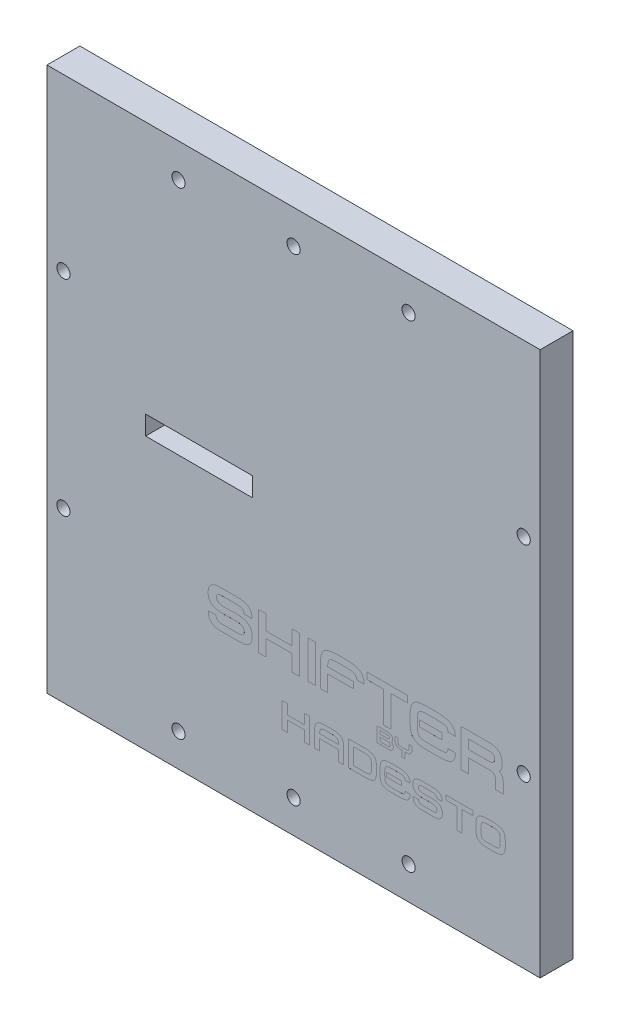
SolidWorks part; units mm, degrees
material "Oak"
ref_plane "Front Plane" through (0, 0, 0) normal (0, 0, 1) x (1, 0, 0)
ref_plane "Top Plane" through (0, 0, 0) normal (0, 1, 0) x (1, 0, 0)
ref_plane "Right Plane" through (0, 0, 0) normal (1, 0, 0) x (0, 0, -1)
sketch "Szkic1" plane through (0, 0, 0) normal (0, 1, 0) x (1, 0, 0)
  line L1 (-75, -5) -> (75, -5)
  line L2 (-75, -5) -> (-75, 5)
  line L3 (-75, 5) -> (75, 5)
  line L4 (75, -5) -> (75, 5)
  line L5 (-75, -5) -> (75, 5) construction
  line L6 (-75, 5) -> (75, -5) construction
  point P0 (0, 0)
extrude "Dodanie-wyciągnięcie1" add sketch "Szkic1" along normal blind 165.5
sketch "Szkic2" plane through (0, 0, 5) normal (0, 0, 1) x (1, 0, 0)
  line L0 (-75, 165.5) -> (-75, 155) construction
  line L1 (-75, 165.5) -> (-75, 0) construction
  line L2 (-35, 155.5) -> (-35, 155.25) construction
  line L3 (0, 155.5) -> (0, 155.25) construction
  line L4 (35, 155.5) -> (35, 155.25) construction
  line L5 (75, 0) -> (75, 10) construction
  line L6 (75, 165.5) -> (75, 0) construction
  line L7 (75, 10) -> (35, 10) construction
  line L8 (35, 10) -> (0, 10) construction
  line L9 (0, 10) -> (-35, 10) construction
  line L10 (-75, 155) -> (-75, 145) construction
  line L11 (-75, 145) -> (-70, 145) construction
  line L12 (-70, 145) -> (-70, 113.75) construction
  line L13 (-70, 113.75) -> (-70, 51.25) construction
  line L14 (75, 10) -> (75, 20) construction
  line L15 (75, 20) -> (70, 20) construction
  line L16 (70, 20) -> (70, 51.25) construction
  line L17 (70, 51.25) -> (70, 113.75) construction
  line L18 (-35, 165.5) -> (-35, 155.5) construction
  line L19 (-75, 165.5) -> (75, 165.5) construction
  line L20 (0, 165.5) -> (0, 155.5) construction
  line L21 (35, 165.5) -> (35, 155.5) construction
  circle A3 centre (-35, 10) radius 2
  circle A4 centre (0, 10) radius 2
  circle A5 centre (35, 10) radius 2
  circle A6 centre (-70, 113.75) radius 2
  circle A7 centre (-70, 51.25) radius 2
  circle A8 centre (70, 113.75) radius 2
  circle A9 centre (70, 51.25) radius 2
  circle A13 centre (-35, 155.25) radius 2
  circle A14 centre (0, 155.25) radius 2
  circle A15 centre (35, 155.25) radius 2
sketch "Szkic3" plane through (0, 0, 5) normal (0, 0, 1) x (1, 0, 0)
  line L0 (-16.5425, 42.8324) -> (-22.1233, 42.8324)
  line L1 (-25.9282, 46.2952) -> (-23.5548, 46.2952)
  line L2 (-21.7883, 44.8332) -> (-16.9713, 44.8332)
  line L3 (-22.1537, 54.2751) -> (-16.8447, 54.2751)
  line L4 (-12.6205, 50.8264) -> (-15.0712, 50.8264)
  line L5 (-17.0205, 52.2883) -> (-22.0272, 52.2883)
  line L6 (1.875, 42.8324) -> (-0.4656, 42.8324)
  line L7 (-0.4656, 42.8324) -> (-0.4656, 47.7431)
  line L8 (-0.4656, 47.7431) -> (-8.3283, 47.7431)
  line L9 (-8.3283, 47.7431) -> (-8.3283, 42.8324)
  line L10 (-8.3283, 42.8324) -> (-10.6689, 42.8324)
  line L11 (-10.6689, 42.8324) -> (-10.6689, 54.2751)
  line L12 (-10.6689, 54.2751) -> (-8.3283, 54.2751)
  line L13 (-8.3283, 54.2751) -> (-8.3283, 49.7275)
  line L14 (-8.3283, 49.7275) -> (-0.4656, 49.7275)
  line L15 (-0.4656, 49.7275) -> (-0.4656, 54.2751)
  line L16 (-0.4656, 54.2751) -> (1.875, 54.2751)
  line L17 (1.875, 54.2751) -> (1.875, 42.8324)
  line L18 (6.706, 42.8324) -> (4.3655, 42.8324)
  line L19 (4.3655, 42.8324) -> (4.3655, 54.2751)
  line L20 (4.3655, 54.2751) -> (6.706, 54.2751)
  line L21 (6.706, 54.2751) -> (6.706, 42.8324)
  line L22 (10.3539, 49.6807) -> (18.205, 49.6807)
  line L23 (18.205, 49.6807) -> (18.205, 47.7759)
  line L24 (18.205, 47.7759) -> (10.3539, 47.7759)
  line L25 (10.3539, 47.7759) -> (10.3539, 42.8324)
  line L26 (10.3539, 42.8324) -> (8.1235, 42.8324)
  line L27 (8.1235, 42.8324) -> (8.1399, 48.767)
  line L28 (13.7089, 54.3384) -> (15.7754, 54.3384)
  line L29 (21.5108, 50.653) -> (19.2944, 50.653)
  line L30 (15.6957, 52.3047) -> (13.8214, 52.3047)
  line L31 (34.6708, 52.2743) -> (29.6477, 52.2743)
  line L32 (29.6477, 52.2743) -> (29.6477, 42.8324)
  line L33 (29.6477, 42.8324) -> (27.3071, 42.8324)
  line L34 (27.3071, 42.8324) -> (27.3071, 52.2743)
  line L35 (27.3071, 52.2743) -> (22.3003, 52.2743)
  line L36 (22.3003, 52.2743) -> (22.3003, 54.2751)
  line L37 (22.3003, 54.2751) -> (34.6708, 54.2751)
  line L38 (34.6708, 54.2751) -> (34.6708, 52.2743)
  line L39 (43.4309, 42.8324) -> (40.9685, 42.8324)
  line L40 (40.999, 54.322) -> (43.4637, 54.322)
  line L41 (49.1991, 50.7467) -> (46.9523, 50.7467)
  line L42 (43.3841, 52.3211) -> (41.1115, 52.3211)
  line L43 (37.6252, 49.5284) -> (37.6276, 47.9235)
  line L44 (41.0623, 44.8004) -> (43.4005, 44.8004)
  line L45 (46.9687, 46.4217) -> (49.2296, 46.4217)
  line L46 (45.1764, 47.7759) -> (38.3328, 47.7993)
  line L47 (38.3328, 47.7993) -> (38.3328, 49.6971)
  line L48 (38.3328, 49.6971) -> (45.1764, 49.6971)
  line L49 (45.1764, 49.6971) -> (45.1764, 47.7759)
  line L50 (63.7883, 42.8324) -> (61.4642, 42.8324)
  line L51 (61.4642, 42.8324) -> (61.4642, 45.016)
  line L52 (59.4516, 47.1082) -> (53.2664, 47.0918)
  line L53 (53.2664, 47.0918) -> (53.2664, 42.8324)
  line L54 (53.2664, 42.8324) -> (50.9891, 42.8324)
  line L55 (50.9891, 42.8324) -> (50.9891, 54.2751)
  line L56 (50.9891, 54.2751) -> (59.2923, 54.2751)
  line L57 (63.7883, 45.7634) -> (63.7883, 42.8324)
  line L58 (59.468, 52.0681) -> (53.2664, 52.0681)
  line L59 (53.2664, 52.0681) -> (53.2664, 49.2988)
  line L60 (53.2664, 49.2988) -> (59.468, 49.2988)
  line L61 (4.9001, 26.251) -> (3.3398, 26.251)
  line L62 (3.3398, 26.251) -> (3.3398, 29.5248)
  line L63 (3.3398, 29.5248) -> (-1.9021, 29.5248)
  line L64 (-1.9021, 29.5248) -> (-1.9021, 26.251)
  line L65 (-1.9021, 26.251) -> (-3.4624, 26.251)
  line L66 (-3.4624, 26.251) -> (-3.4624, 33.8794)
  line L67 (-3.4624, 33.8794) -> (-1.9021, 33.8794)
  line L68 (-1.9021, 33.8794) -> (-1.9021, 30.8477)
  line L69 (-1.9021, 30.8477) -> (3.3398, 30.8477)
  line L70 (3.3398, 30.8477) -> (3.3398, 33.8794)
  line L71 (3.3398, 33.8794) -> (4.9001, 33.8794)
  line L72 (4.9001, 33.8794) -> (4.9001, 26.251)
  line L73 (7.9396, 30.8477) -> (13.6922, 30.8477)
  line L74 (11.5133, 32.5455) -> (9.9983, 32.5455)
  line L75 (13.7016, 29.5248) -> (7.9412, 29.5248)
  line L76 (7.9412, 29.5248) -> (7.9412, 26.251)
  line L77 (7.9412, 26.251) -> (6.3808, 26.251)
  line L78 (6.3808, 26.251) -> (6.3808, 30.7587)
  line L79 (9.828, 33.8794) -> (11.7039, 33.8794)
  line L80 (15.2635, 30.7587) -> (15.2635, 26.251)
  line L81 (15.2635, 26.251) -> (13.7016, 26.251)
  line L82 (13.7016, 26.251) -> (13.7016, 29.5248)
  line L83 (21.9892, 26.24) -> (16.6552, 26.24)
  line L84 (16.6552, 26.24) -> (16.6552, 33.8794)
  line L85 (16.6552, 33.8794) -> (21.8096, 33.8794)
  line L86 (23.7011, 29.6138) -> (23.7011, 30.5463)
  line L87 (21.7252, 32.5549) -> (18.2265, 32.5549)
  line L88 (18.2265, 32.5549) -> (18.2265, 27.5739)
  line L89 (18.2265, 27.5739) -> (21.8205, 27.5739)
  line L90 (31.6044, 26.251) -> (29.9629, 26.251)
  line L91 (29.9832, 33.9107) -> (31.6263, 33.9107)
  line L92 (35.4499, 31.5272) -> (33.952, 31.5272)
  line L93 (31.5732, 32.5768) -> (30.0581, 32.5768)
  line L94 (27.734, 30.715) -> (27.7355, 29.645)
  line L95 (30.0253, 27.563) -> (31.5841, 27.563)
  line L96 (33.963, 28.6438) -> (35.4702, 28.6438)
  line L97 (32.7681, 29.5466) -> (28.2057, 29.5623)
  line L98 (28.2057, 29.5623) -> (28.2057, 30.8337)
  line L99 (28.2057, 30.8337) -> (32.7681, 30.8274)
  line L100 (32.7681, 30.8274) -> (32.7681, 29.5466)
  line L101 (42.6036, 26.251) -> (38.883, 26.251)
  line L102 (36.3465, 28.5595) -> (37.9287, 28.5595)
  line L103 (39.1064, 27.5848) -> (42.3177, 27.5848)
  line L104 (38.8627, 33.8794) -> (42.4021, 33.8794)
  line L105 (45.2182, 31.5803) -> (43.5845, 31.5803)
  line L106 (42.2849, 32.5549) -> (38.9471, 32.5549)
  line L107 (54.5539, 32.5455) -> (51.2051, 32.5455)
  line L108 (51.2051, 32.5455) -> (51.2051, 26.251)
  line L109 (51.2051, 26.251) -> (49.6447, 26.251)
  line L110 (49.6447, 26.251) -> (49.6447, 32.5455)
  line L111 (49.6447, 32.5455) -> (46.3069, 32.5455)
  line L112 (46.3069, 32.5455) -> (46.3069, 33.8794)
  line L113 (46.3069, 33.8794) -> (54.5539, 33.8794)
  line L114 (54.5539, 33.8794) -> (54.5539, 32.5455)
  line L115 (60.5002, 26.251) -> (59.1335, 26.251)
  line L116 (59.1538, 33.9216) -> (60.5111, 33.9216)
  line L117 (62.8477, 29.6888) -> (62.8477, 30.3979)
  line L118 (60.458, 32.4815) -> (59.2287, 32.4815)
  line L119 (57.0014, 30.3885) -> (57.0014, 29.6778)
  line L120 (59.1975, 27.6692) -> (60.4783, 27.6692)
  spline S0 degree 3 poles (-12.5713, 46.2577) (-12.5722, 45.9664) (-12.5971, 45.5408) (-12.7128, 45.0029) (-12.83, 44.6437) (-12.9796, 44.3159) (-13.2238, 43.9226) (-13.462, 43.6722) (-13.6397, 43.5306) knots 0 0 0 0 0.288468 0.419708 0.543339 0.661573 0.775414 1 1 1 1
  spline S1 degree 3 poles (-13.6397, 43.5306) (-13.7956, 43.405) (-14.0684, 43.2543) (-14.4678, 43.0951) (-14.8161, 43.0021) (-15.1968, 42.9241) (-15.7757, 42.8517) (-16.2289, 42.8331) (-16.5425, 42.8324) knots 0 0 0 0 0.196905 0.306371 0.424122 0.552441 0.690159 1 1 1 1
  spline S2 degree 3 poles (-22.1233, 42.8324) (-22.422, 42.8344) (-22.8582, 42.854) (-23.4142, 42.9477) (-23.7888, 43.04) (-24.1336, 43.1621) (-24.4483, 43.3123) (-24.7349, 43.4871) (-24.9872, 43.6949) (-25.2139, 43.9236) (-25.4089, 44.1827) (-25.5687, 44.4703) (-25.7049, 44.7826) (-25.8063, 45.1234) (-25.9058, 45.628) (-25.9273, 46.0244) (-25.9282, 46.2952) knots 0 0 0 0 0.151922 0.221135 0.286192 0.347689 0.406613 0.463101 0.517821 0.572256 0.62638 0.681995 0.739047 0.799173 0.862284 1 1 1 1
  spline S3 degree 3 poles (-23.5548, 46.2952) (-23.5548, 46.1808) (-23.5432, 46.0128) (-23.4942, 45.8007) (-23.4488, 45.6557) (-23.3843, 45.5245) (-23.3085, 45.4034) (-23.2203, 45.2915) (-23.1122, 45.1968) (-22.9959, 45.1079) (-22.8624, 45.037) (-22.7184, 44.9718) (-22.5586, 44.9215) (-22.3854, 44.8818) (-22.1277, 44.8442) (-21.9269, 44.8304) (-21.7883, 44.8332) knots 0 0 0 0 0.130945 0.191386 0.248712 0.304229 0.357995 0.411968 0.466331 0.521876 0.579035 0.638606 0.702429 0.770232 0.841588 1 1 1 1
  spline S4 degree 3 poles (-16.9713, 44.8332) (-16.8211, 44.8336) (-16.6038, 44.8417) (-16.3246, 44.8653) (-16.1399, 44.8953) (-15.9696, 44.9248) (-15.7743, 44.9853) (-15.6357, 45.0343) (-15.5538, 45.0816) knots 0 0 0 0 0.310015 0.449363 0.57828 0.696618 0.805875 1 1 1 1
  spline S5 degree 3 poles (-15.5538, 45.0816) (-15.4606, 45.1333) (-15.3318, 45.2304) (-15.1981, 45.3974) (-15.1156, 45.5375) (-15.0561, 45.6959) (-14.9882, 45.9333) (-14.9809, 46.1266) (-14.9775, 46.2577) knots 0 0 0 0 0.232178 0.345784 0.463842 0.584405 0.713048 1 1 1 1
  spline S6 degree 3 poles (-14.9775, 46.2577) (-14.9803, 46.4053) (-15.0015, 46.6269) (-15.1181, 46.8905) (-15.2304, 47.0659) (-15.3779, 47.2214) (-15.6263, 47.4094) (-15.8492, 47.5073) (-16.006, 47.5604) knots 0 0 0 0 0.249245 0.364726 0.480164 0.596826 0.721947 1 1 1 1
  spline S7 degree 3 poles (-16.006, 47.5604) (-16.1277, 47.6026) (-16.3234, 47.6529) (-16.6003, 47.7037) (-16.8364, 47.7359) (-17.0927, 47.7614) (-17.4737, 47.7879) (-17.7702, 47.7891) (-17.974, 47.7923) knots 0 0 0 0 0.194055 0.304223 0.424293 0.553298 0.692568 1 1 1 1
  spline S8 degree 3 poles (-17.974, 47.7923) (-18.1958, 47.7915) (-18.5622, 47.7871) (-19.0955, 47.7678) (-19.5742, 47.7525) (-20.053, 47.7372) (-20.5893, 47.7177) (-20.9589, 47.7135) (-21.1838, 47.7127) knots 0 0 0 0 0.207249 0.342309 0.498541 0.654773 0.789832 1 1 1 1
  spline S9 degree 3 poles (-21.1838, 47.7127) (-21.5213, 47.7157) (-22.0113, 47.7254) (-22.6409, 47.7824) (-23.0635, 47.8443) (-23.4542, 47.9175) (-23.9144, 48.0333) (-24.2341, 48.1563) (-24.431, 48.2515) knots 0 0 0 0 0.305274 0.442866 0.571301 0.691383 0.802203 1 1 1 1
  spline S10 degree 3 poles (-24.431, 48.2515) (-24.6786, 48.375) (-25.0201, 48.6072) (-25.3906, 49.003) (-25.6101, 49.3368) (-25.783, 49.7059) (-25.9488, 50.267) (-25.9946, 50.717) (-25.9914, 51.0255) knots 0 0 0 0 0.24616 0.363762 0.480638 0.600407 0.725359 1 1 1 1
  spline S11 degree 3 poles (-25.9914, 51.0255) (-25.9927, 51.3039) (-25.9626, 51.7098) (-25.8472, 52.2226) (-25.7313, 52.5649) (-25.5783, 52.8745) (-25.3286, 53.2434) (-25.0931, 53.4792) (-24.9137, 53.6074) knots 0 0 0 0 0.287332 0.417925 0.54153 0.659382 0.773151 1 1 1 1
  spline S12 degree 3 poles (-24.9137, 53.6074) (-24.7536, 53.7243) (-24.4854, 53.8727) (-24.0922, 54.0226) (-23.7601, 54.1144) (-23.3992, 54.1874) (-22.8619, 54.2559) (-22.4425, 54.2784) (-22.1537, 54.2751) knots 0 0 0 0 0.205829 0.317156 0.436985 0.563785 0.699798 1 1 1 1
  spline S13 degree 3 poles (-16.8447, 54.2751) (-16.514, 54.2729) (-16.032, 54.2538) (-15.4167, 54.1597) (-15.0024, 54.0678) (-14.6215, 53.9455) (-14.2721, 53.7988) (-13.9567, 53.623) (-13.6744, 53.4194) (-13.4246, 53.1899) (-13.2094, 52.9306) (-13.0252, 52.6466) (-12.8778, 52.333) (-12.7598, 51.9949) (-12.6489, 51.4922) (-12.6205, 51.0969) (-12.6205, 50.8264) knots 0 0 0 0 0.159185 0.231381 0.299177 0.363087 0.423506 0.481188 0.536339 0.590564 0.643901 0.697977 0.752917 0.810175 0.869863 1 1 1 1
  spline S14 degree 3 poles (-15.0712, 50.8264) (-15.0691, 50.9412) (-15.0855, 51.1087) (-15.1351, 51.3221) (-15.19, 51.4655) (-15.2574, 51.5988) (-15.3439, 51.7184) (-15.4411, 51.8304) (-15.5589, 51.9255) (-15.6873, 52.0143) (-15.8347, 52.085) (-15.9946, 52.1496) (-16.1706, 52.2) (-16.3616, 52.2402) (-16.646, 52.2769) (-16.8677, 52.2916) (-17.0205, 52.2883) knots 0 0 0 0 0.123736 0.18099 0.235951 0.289117 0.341746 0.394885 0.448749 0.504633 0.563073 0.624754 0.690648 0.760424 0.8353 1 1 1 1
  spline S15 degree 3 poles (-22.0272, 52.2883) (-22.2371, 52.2869) (-22.5405, 52.2592) (-22.8972, 52.1172) (-23.1063, 51.9741) (-23.2671, 51.7854) (-23.4277, 51.4644) (-23.4554, 51.1829) (-23.4587, 50.9927) knots 0 0 0 0 0.286177 0.406449 0.517602 0.626596 0.73942 1 1 1 1
  spline S16 degree 3 poles (-23.4587, 50.9927) (-23.457, 50.8857) (-23.4397, 50.7253) (-23.3611, 50.5294) (-23.2838, 50.394) (-23.1812, 50.2708) (-23.0548, 50.1609) (-22.908, 50.0593) (-22.739, 49.9686) (-22.5482, 49.8892) (-22.3348, 49.8213) (-22.0996, 49.7644) (-21.8419, 49.7141) (-21.5617, 49.6777) (-21.1439, 49.6434) (-20.8193, 49.6322) (-20.5957, 49.6338) knots 0 0 0 0 0.091833 0.135566 0.179508 0.224525 0.271785 0.322124 0.376754 0.435361 0.498446 0.567863 0.641921 0.722688 0.809065 1 1 1 1
  spline S17 degree 3 poles (-20.5957, 49.6338) (-20.3847, 49.6313) (-20.0411, 49.645) (-19.5468, 49.6639) (-19.1135, 49.688) (-18.6816, 49.71) (-18.1961, 49.7357) (-17.86, 49.7408) (-17.6554, 49.7439) knots 0 0 0 0 0.215037 0.3505 0.504367 0.657438 0.791346 1 1 1 1
  spline S18 degree 3 poles (-17.6554, 49.7439) (-17.3013, 49.7442) (-16.7871, 49.7276) (-16.1262, 49.6657) (-15.6825, 49.5961) (-15.2721, 49.5153) (-14.7902, 49.377) (-14.4514, 49.2483) (-14.2465, 49.1371) knots 0 0 0 0 0.304045 0.441512 0.569747 0.689567 0.800388 1 1 1 1
  spline S19 degree 3 poles (-14.2465, 49.1371) (-13.9801, 49.0015) (-13.6163, 48.7484) (-13.2176, 48.3282) (-12.9809, 47.9812) (-12.7966, 47.5998) (-12.617, 47.0288) (-12.5698, 46.5702) (-12.5713, 46.2577) knots 0 0 0 0 0.254404 0.37397 0.491718 0.610756 0.733649 1 1 1 1
  spline S20 degree 3 poles (8.1399, 48.767) (8.1362, 49.1295) (8.1517, 49.6538) (8.1869, 50.3257) (8.2303, 50.7693) (8.2805, 51.1728) (8.3587, 51.6344) (8.4451, 51.9562) (8.5124, 52.1548) knots 0 0 0 0 0.317801 0.45977 0.589762 0.708489 0.816214 1 1 1 1
  spline S21 degree 3 poles (8.5124, 52.1548) (8.5823, 52.3536) (8.7152, 52.6374) (8.9421, 52.982) (9.1387, 53.211) (9.3602, 53.4154) (9.6921, 53.6615) (9.973, 53.8027) (10.1688, 53.8815) knots 0 0 0 0 0.255571 0.378596 0.499596 0.620993 0.743641 1 1 1 1
  spline S22 degree 3 poles (10.1688, 53.8815) (10.3771, 53.968) (10.7195, 54.064) (11.2069, 54.1671) (11.6307, 54.227) (12.0937, 54.2803) (12.7906, 54.3259) (13.3339, 54.3388) (13.7089, 54.3384) knots 0 0 0 0 0.188097 0.296817 0.416308 0.545737 0.686461 1 1 1 1
  spline S23 degree 3 poles (15.7754, 54.3384) (16.2552, 54.3384) (16.9455, 54.3195) (17.8243, 54.2409) (18.3919, 54.1568) (18.9002, 54.0541) (19.464, 53.8884) (19.8483, 53.725) (20.0676, 53.5816) knots 0 0 0 0 0.326658 0.469759 0.60036 0.717142 0.822452 1 1 1 1
  spline S24 degree 3 poles (20.0676, 53.5816) (20.2708, 53.4493) (20.5514, 53.2043) (20.848, 52.7998) (21.047, 52.4533) (21.2078, 52.0614) (21.3982, 51.4654) (21.4729, 50.9844) (21.5108, 50.653) knots 0 0 0 0 0.215512 0.327131 0.444654 0.569708 0.702963 1 1 1 1
  spline S25 degree 3 poles (19.2944, 50.653) (19.2538, 50.8306) (19.1749, 51.0836) (19.0275, 51.3916) (18.8996, 51.5854) (18.756, 51.7535) (18.5427, 51.944) (18.3519, 52.0428) (18.219, 52.0892) knots 0 0 0 0 0.291344 0.422029 0.544637 0.661528 0.774774 1 1 1 1
  spline S26 degree 3 poles (18.219, 52.0892) (18.0932, 52.1354) (17.8772, 52.1774) (17.5622, 52.2242) (17.2667, 52.2535) (16.9315, 52.2767) (16.4035, 52.298) (15.9871, 52.3079) (15.6957, 52.3047) knots 0 0 0 0 0.157647 0.259244 0.376059 0.508256 0.65595 1 1 1 1
  spline S27 degree 3 poles (13.8214, 52.3047) (13.498, 52.3039) (13.0366, 52.294) (12.4539, 52.2529) (12.0876, 52.2099) (11.7694, 52.1513) (11.4332, 52.0702) (11.2106, 51.9812) (11.0896, 51.8994) knots 0 0 0 0 0.347896 0.496132 0.628134 0.744282 0.843901 1 1 1 1
  spline S28 degree 3 poles (11.0896, 51.8994) (10.9672, 51.823) (10.8144, 51.6538) (10.6572, 51.3775) (10.5595, 51.1174) (10.4778, 50.8178) (10.3906, 50.3365) (10.3615, 49.951) (10.3539, 49.6807) knots 0 0 0 0 0.177191 0.278825 0.393353 0.521096 0.66412 1 1 1 1
  spline S29 degree 3 poles (49.2296, 46.4217) (49.2301, 46.0648) (49.1922, 45.5471) (49.0255, 44.9035) (48.8535, 44.4908) (48.6344, 44.1265) (48.2729, 43.7059) (47.9248, 43.4733) (47.6762, 43.3549) knots 0 0 0 0 0.294114 0.424501 0.54583 0.660956 0.773103 1 1 1 1
  spline S30 degree 3 poles (47.6762, 43.3549) (47.4649, 43.2548) (47.1022, 43.1355) (46.5648, 43.0284) (46.0664, 42.9576) (45.5023, 42.8987) (44.6164, 42.847) (43.9185, 42.829) (43.4309, 42.8324) knots 0 0 0 0 0.16271 0.264982 0.381608 0.513497 0.660216 1 1 1 1
  spline S31 degree 3 poles (40.9685, 42.8324) (40.6006, 42.8331) (40.0683, 42.8441) (39.3856, 42.8848) (38.933, 42.9282) (38.5214, 42.9874) (38.0474, 43.0717) (37.7161, 43.1615) (37.5128, 43.2377) knots 0 0 0 0 0.315853 0.456902 0.58691 0.70608 0.813768 1 1 1 1
  spline S32 degree 3 poles (37.5128, 43.2377) (37.3157, 43.308) (37.0371, 43.4466) (36.699, 43.6791) (36.4767, 43.8806) (36.2743, 44.102) (36.0373, 44.4384) (35.8937, 44.7167) (35.8212, 44.9152) knots 0 0 0 0 0.254655 0.377777 0.499186 0.619886 0.74278 1 1 1 1
  spline S33 degree 3 poles (35.8212, 44.9152) (35.744, 45.1184) (35.6573, 45.4504) (35.5668, 45.9233) (35.5137, 46.3359) (35.4646, 46.7879) (35.4262, 47.4708) (35.4136, 48.003) (35.4135, 48.371) knots 0 0 0 0 0.186213 0.294014 0.413081 0.543143 0.684177 1 1 1 1
  spline S34 degree 3 poles (35.4135, 48.371) (35.4129, 48.7639) (35.4211, 49.3305) (35.4592, 50.0561) (35.499, 50.5326) (35.5472, 50.9657) (35.6223, 51.4555) (35.7024, 51.7975) (35.7673, 52.0072) knots 0 0 0 0 0.321609 0.463729 0.594587 0.712971 0.820379 1 1 1 1
  spline S35 degree 3 poles (35.7673, 52.0072) (35.8342, 52.2208) (35.9606, 52.5271) (36.1869, 52.896) (36.3792, 53.14) (36.5946, 53.3595) (36.9232, 53.6156) (37.2, 53.7665) (37.3956, 53.8464) knots 0 0 0 0 0.264263 0.388826 0.509594 0.630161 0.750928 1 1 1 1
  spline S36 degree 3 poles (37.3956, 53.8464) (37.6048, 53.9369) (37.9501, 54.0386) (38.4431, 54.1434) (38.8728, 54.2071) (39.3449, 54.2584) (40.0578, 54.3088) (40.6146, 54.3235) (40.999, 54.322) knots 0 0 0 0 0.186673 0.294794 0.413465 0.543078 0.684474 1 1 1 1
  spline S37 degree 3 poles (43.4637, 54.322) (43.9389, 54.3202) (44.6259, 54.3006) (45.5021, 54.2086) (46.0786, 54.1123) (46.6018, 53.9935) (47.2015, 53.8016) (47.6117, 53.611) (47.852, 53.4527) knots 0 0 0 0 0.314845 0.454824 0.583342 0.70181 0.80996 1 1 1 1
  spline S38 degree 3 poles (47.852, 53.4527) (48.0678, 53.3135) (48.367, 53.07) (48.6792, 52.6693) (48.8709, 52.3436) (49.0189, 51.9863) (49.1627, 51.4559) (49.1995, 51.0341) (49.1991, 50.7467) knots 0 0 0 0 0.24395 0.361591 0.480106 0.601286 0.727242 1 1 1 1
  spline S39 degree 3 poles (46.9523, 50.7467) (46.9502, 50.9142) (46.9332, 51.1604) (46.8293, 51.4572) (46.7328, 51.6487) (46.5996, 51.8104) (46.383, 51.9988) (46.1819, 52.0917) (46.0409, 52.136) knots 0 0 0 0 0.281221 0.405304 0.523085 0.637091 0.752607 1 1 1 1
  spline S40 degree 3 poles (46.0409, 52.136) (45.9091, 52.1746) (45.6855, 52.2155) (45.3572, 52.2511) (45.047, 52.2765) (44.6932, 52.2978) (44.1339, 52.3156) (43.6926, 52.3229) (43.3841, 52.3211) knots 0 0 0 0 0.154176 0.25489 0.371156 0.503933 0.653245 1 1 1 1
  spline S41 degree 3 poles (41.1115, 52.3211) (40.7849, 52.3205) (40.3181, 52.3101) (39.7283, 52.2695) (39.3559, 52.226) (39.0321, 52.168) (38.6878, 52.0857) (38.4589, 51.9975) (38.3328, 51.9158) knots 0 0 0 0 0.345644 0.493985 0.62552 0.742253 0.841884 1 1 1 1
  spline S42 degree 3 poles (38.3328, 51.9158) (38.2091, 51.8334) (38.0486, 51.6568) (37.8984, 51.3593) (37.8023, 51.0805) (37.7223, 50.7577) (37.6468, 50.2363) (37.6274, 49.8202) (37.6252, 49.5284) knots 0 0 0 0 0.172183 0.272745 0.386756 0.515244 0.659814 1 1 1 1
  spline S43 degree 3 poles (37.6276, 47.9235) (37.6269, 47.5931) (37.6356, 47.1215) (37.707, 46.5311) (37.7779, 46.1664) (37.8697, 45.8533) (38.015, 45.5259) (38.1684, 45.3238) (38.2953, 45.2315) knots 0 0 0 0 0.347585 0.494831 0.624602 0.737837 0.837036 1 1 1 1
  spline S44 degree 3 poles (38.2953, 45.2315) (38.4155, 45.1459) (38.6399, 45.0528) (38.9783, 44.962) (39.3011, 44.9024) (39.672, 44.8566) (40.2641, 44.8127) (40.7333, 44.7996) (41.0623, 44.8004) knots 0 0 0 0 0.155206 0.255592 0.370997 0.502802 0.651395 1 1 1 1
  spline S45 degree 3 poles (43.4005, 44.8004) (43.716, 44.7987) (44.1659, 44.8059) (44.7346, 44.8237) (45.0915, 44.8451) (45.4025, 44.8702) (45.727, 44.9057) (45.946, 44.9463) (46.0737, 44.9855) knots 0 0 0 0 0.352452 0.50258 0.635404 0.751817 0.851039 1 1 1 1
  spline S46 degree 3 poles (46.0737, 44.9855) (46.2148, 45.0281) (46.4171, 45.119) (46.6311, 45.3116) (46.761, 45.4792) (46.8591, 45.6759) (46.9534, 45.9896) (46.9724, 46.2452) (46.9687, 46.4217) knots 0 0 0 0 0.241561 0.354455 0.467197 0.585823 0.711271 1 1 1 1
  spline S47 degree 3 poles (61.4642, 45.016) (61.4636, 45.1911) (61.4535, 45.4451) (61.4041, 45.767) (61.3594, 45.9795) (61.2953, 46.1707) (61.2184, 46.3419) (61.1291, 46.4951) (61.0227, 46.6278) (60.8978, 46.7429) (60.753, 46.8415) (60.588, 46.9262) (60.4013, 46.9937) (60.193, 47.0445) (59.8754, 47.0951) (59.6247, 47.1097) (59.4516, 47.1082) knots 0 0 0 0 0.155012 0.224176 0.287859 0.346836 0.402173 0.453586 0.503209 0.552091 0.603248 0.657619 0.715748 0.778405 0.846994 1 1 1 1
  spline S48 degree 3 poles (59.2923, 54.2751) (59.6295, 54.2778) (60.117, 54.2535) (60.7382, 54.1669) (61.1482, 54.0808) (61.5184, 53.9622) (61.9492, 53.7828) (62.2348, 53.5983) (62.399, 53.4551) knots 0 0 0 0 0.308563 0.445716 0.573699 0.691456 0.800969 1 1 1 1
  spline S49 degree 3 poles (62.399, 53.4551) (62.5743, 53.2988) (62.8032, 53.0231) (63.0434, 52.604) (63.1876, 52.2503) (63.3035, 51.8647) (63.409, 51.2847) (63.4408, 50.8299) (63.4392, 50.5171) knots 0 0 0 0 0.218919 0.332324 0.450085 0.574982 0.707932 1 1 1 1
  spline S50 degree 3 poles (63.4392, 50.5171) (63.4365, 50.2364) (63.4175, 49.8326) (63.3056, 49.3339) (63.1981, 49.0219) (63.0517, 48.7575) (62.8215, 48.464) (62.5884, 48.3126) (62.4224, 48.2468) knots 0 0 0 0 0.319412 0.455762 0.579144 0.692631 0.7973 1 1 1 1
  spline S51 degree 3 poles (62.4224, 48.2468) (62.5319, 48.2204) (62.6935, 48.1711) (62.8867, 48.0636) (63.0224, 47.9758) (63.1442, 47.8684) (63.257, 47.7483) (63.361, 47.6153) (63.4494, 47.4653) (63.5298, 47.3026) (63.5994, 47.1255) (63.658, 46.9334) (63.7072, 46.7277) (63.7444, 46.507) (63.7785, 46.1844) (63.7898, 45.9346) (63.7883, 45.7634) knots 0 0 0 0 0.109953 0.162653 0.214708 0.266963 0.320181 0.374897 0.430803 0.489254 0.55134 0.615754 0.684501 0.756956 0.833401 1 1 1 1
  spline S52 degree 3 poles (59.468, 49.2988) (59.7135, 49.3026) (60.0682, 49.328) (60.4874, 49.4866) (60.7302, 49.648) (60.9207, 49.8565) (61.1052, 50.2141) (61.1471, 50.5265) (61.1455, 50.7397) knots 0 0 0 0 0.292647 0.414933 0.527702 0.635233 0.746266 1 1 1 1
  spline S53 degree 3 poles (61.1455, 50.7397) (61.1478, 50.9369) (61.1035, 51.2275) (60.9195, 51.5564) (60.7283, 51.748) (60.4847, 51.8935) (60.067, 52.0435) (59.7129, 52.0643) (59.468, 52.0681) knots 0 0 0 0 0.243091 0.351382 0.457894 0.571596 0.697254 1 1 1 1
  spline S54 degree 3 poles (13.6922, 30.8477) (13.6926, 31.0165) (13.6755, 31.2579) (13.6252, 31.5621) (13.573, 31.7545) (13.5056, 31.9225) (13.4018, 32.1088) (13.2935, 32.2205) (13.2127, 32.2769) knots 0 0 0 0 0.324044 0.46416 0.591814 0.70624 0.811083 1 1 1 1
  spline S55 degree 3 poles (13.2127, 32.2769) (13.1367, 32.3293) (12.9975, 32.3881) (12.7881, 32.4454) (12.5894, 32.4818) (12.3621, 32.5111) (12.0001, 32.5382) (11.7139, 32.5451) (11.5133, 32.5455) knots 0 0 0 0 0.158283 0.258942 0.374128 0.506345 0.654083 1 1 1 1
  spline S56 degree 3 poles (9.9983, 32.5455) (9.8087, 32.5445) (9.5374, 32.5393) (9.1947, 32.5097) (8.9784, 32.4784) (8.7884, 32.4408) (8.5851, 32.3806) (8.449, 32.3208) (8.3754, 32.266) knots 0 0 0 0 0.341247 0.488 0.61865 0.734417 0.836097 1 1 1 1
  spline S57 degree 3 poles (8.3754, 32.266) (8.3013, 32.2111) (8.201, 32.1026) (8.1095, 31.92) (8.0483, 31.754) (8.0009, 31.5633) (7.9537, 31.2593) (7.9419, 31.0172) (7.9396, 30.8477) knots 0 0 0 0 0.180375 0.283893 0.398091 0.526429 0.667896 1 1 1 1
  spline S58 degree 3 poles (6.3808, 30.7587) (6.3809, 30.9097) (6.3863, 31.1319) (6.4077, 31.4212) (6.4287, 31.6246) (6.4591, 31.8177) (6.493, 32.0012) (6.533, 32.1752) (6.5823, 32.3388) (6.6344, 32.4936) (6.6942, 32.6388) (6.7612, 32.7736) (6.8329, 32.9002) (6.9129, 33.0158) (7.0264, 33.1556) (7.1201, 33.251) (7.1899, 33.3046) knots 0 0 0 0 0.164418 0.241696 0.315791 0.38688 0.454344 0.518949 0.58099 0.640308 0.696716 0.751711 0.804006 0.854935 0.904496 1 1 1 1
  spline S59 degree 3 poles (7.1899, 33.3046) (7.3198, 33.4093) (7.5515, 33.5388) (7.9014, 33.6616) (8.2133, 33.7425) (8.5634, 33.8034) (9.1045, 33.8661) (9.5316, 33.878) (9.828, 33.8794) knots 0 0 0 0 0.181811 0.287673 0.404741 0.533691 0.675806 1 1 1 1
  spline S60 degree 3 poles (11.7039, 33.8794) (12.0049, 33.8773) (12.439, 33.8673) (12.9894, 33.8019) (13.3459, 33.7388) (13.6651, 33.6597) (14.021, 33.5305) (14.2588, 33.4009) (14.392, 33.2937) knots 0 0 0 0 0.323218 0.46499 0.594403 0.711468 0.817329 1 1 1 1
  spline S61 degree 3 poles (14.392, 33.2937) (14.5412, 33.1757) (14.7359, 32.955) (14.9315, 32.6065) (15.0556, 32.3051) (15.1494, 31.9678) (15.241, 31.4506) (15.263, 31.0415) (15.2635, 30.7587) knots 0 0 0 0 0.20546 0.315073 0.43164 0.557677 0.693518 1 1 1 1
  spline S62 degree 3 poles (25.263, 29.5716) (25.2649, 29.2833) (25.2462, 28.8676) (25.1784, 28.3398) (25.1095, 27.9961) (25.0178, 27.6892) (24.876, 27.3406) (24.7327, 27.1099) (24.6164, 26.9819) knots 0 0 0 0 0.317702 0.457736 0.585992 0.703413 0.810158 1 1 1 1
  spline S63 degree 3 poles (24.6164, 26.9819) (24.5602, 26.9171) (24.4616, 26.831) (24.3173, 26.7284) (24.1989, 26.654) (24.0682, 26.5895) (23.9286, 26.5282) (23.7798, 26.472) (23.6198, 26.4239) (23.4506, 26.38) (23.2705, 26.3434) (23.0817, 26.3096) (22.8824, 26.2857) (22.6736, 26.2656) (22.3749, 26.2431) (22.1454, 26.2418) (21.9892, 26.24) knots 0 0 0 0 0.091644 0.139592 0.1894 0.241249 0.29541 0.352558 0.411446 0.474174 0.539655 0.608107 0.679455 0.754496 0.832729 1 1 1 1
  spline S64 degree 3 poles (21.8096, 33.8794) (22.0644, 33.8791) (22.4339, 33.8671) (22.9057, 33.8129) (23.2192, 33.7617) (23.504, 33.6909) (23.8358, 33.5842) (24.0617, 33.4724) (24.1962, 33.3843) knots 0 0 0 0 0.30972 0.448551 0.576905 0.695522 0.804763 1 1 1 1
  spline S65 degree 3 poles (24.1962, 33.3843) (24.3173, 33.3059) (24.4859, 33.1698) (24.678, 32.9551) (24.8031, 32.7776) (24.9108, 32.584) (25.0378, 32.3002) (25.0974, 32.0693) (25.1287, 31.9114) knots 0 0 0 0 0.241211 0.360252 0.480825 0.603645 0.730356 1 1 1 1
  spline S66 degree 3 poles (25.1287, 31.9114) (25.1533, 31.78) (25.1864, 31.5659) (25.2106, 31.2581) (25.2328, 30.9813) (25.2449, 30.6734) (25.2612, 30.2002) (25.2631, 29.8293) (25.263, 29.5716) knots 0 0 0 0 0.170985 0.276567 0.394702 0.525969 0.670487 1 1 1 1
  spline S67 degree 3 poles (23.7011, 30.5463) (23.7019, 30.7299) (23.6898, 30.9931) (23.6509, 31.3266) (23.6068, 31.5395) (23.553, 31.7286) (23.4871, 31.8936) (23.4067, 32.0335) (23.3127, 32.1521) (23.1972, 32.2494) (23.0608, 32.3336) (22.898, 32.4) (22.7125, 32.4591) (22.5006, 32.5003) (22.1701, 32.5472) (21.9075, 32.5537) (21.7252, 32.5549) knots 0 0 0 0 0.163968 0.235228 0.299821 0.35797 0.410753 0.458068 0.501732 0.545277 0.592271 0.644375 0.701903 0.766041 0.836961 1 1 1 1
  spline S68 degree 3 poles (21.8205, 27.5739) (22.0065, 27.5747) (22.2735, 27.5823) (22.6092, 27.6274) (22.8207, 27.6724) (23.0054, 27.727) (23.205, 27.8161) (23.3299, 27.9099) (23.3949, 27.9831) knots 0 0 0 0 0.33456 0.479099 0.608331 0.7229 0.824679 1 1 1 1
  spline S69 degree 3 poles (23.3949, 27.9831) (23.4525, 28.0548) (23.5234, 28.1872) (23.5846, 28.3917) (23.6294, 28.5818) (23.6596, 28.8005) (23.6962, 29.1468) (23.6997, 29.4217) (23.7011, 29.6138) knots 0 0 0 0 0.163305 0.264522 0.379735 0.511061 0.657458 1 1 1 1
  spline S70 degree 3 poles (35.4702, 28.6438) (35.4706, 28.4059) (35.4453, 28.0608) (35.3342, 27.6317) (35.2195, 27.3566) (35.0734, 27.1137) (34.8324, 26.8333) (34.6004, 26.6782) (34.4347, 26.5993) knots 0 0 0 0 0.294114 0.424501 0.54583 0.660956 0.773103 1 1 1 1
  spline S71 degree 3 poles (34.4347, 26.5993) (34.2938, 26.5325) (34.052, 26.4531) (33.6937, 26.3817) (33.3615, 26.3344) (32.9854, 26.2952) (32.3948, 26.2607) (31.9295, 26.2487) (31.6044, 26.251) knots 0 0 0 0 0.16271 0.264982 0.381608 0.513497 0.660216 1 1 1 1
  spline S72 degree 3 poles (29.9629, 26.251) (29.7176, 26.2514) (29.3627, 26.2587) (28.9076, 26.2859) (28.6058, 26.3149) (28.3314, 26.3543) (28.0154, 26.4105) (27.7946, 26.4704) (27.659, 26.5212) knots 0 0 0 0 0.315853 0.456902 0.58691 0.70608 0.813768 1 1 1 1
  spline S73 degree 3 poles (27.659, 26.5212) (27.5277, 26.568) (27.3419, 26.6605) (27.1165, 26.8154) (26.9683, 26.9498) (26.8334, 27.0974) (26.6754, 27.3216) (26.5797, 27.5072) (26.5313, 27.6395) knots 0 0 0 0 0.254655 0.377777 0.499186 0.619886 0.74278 1 1 1 1
  spline S74 degree 3 poles (26.5313, 27.6395) (26.4799, 27.775) (26.4221, 27.9963) (26.3617, 28.3116) (26.3263, 28.5866) (26.2936, 28.8879) (26.268, 29.3433) (26.2596, 29.698) (26.2595, 29.9434) knots 0 0 0 0 0.186213 0.294014 0.413081 0.543143 0.684177 1 1 1 1
  spline S75 degree 3 poles (26.2595, 29.9434) (26.2591, 30.2053) (26.2645, 30.5831) (26.29, 31.0667) (26.3165, 31.3844) (26.3486, 31.6732) (26.3987, 31.9997) (26.4521, 32.2277) (26.4954, 32.3675) knots 0 0 0 0 0.321609 0.463729 0.594587 0.712971 0.820379 1 1 1 1
  spline S76 degree 3 poles (26.4954, 32.3675) (26.54, 32.5099) (26.6242, 32.7141) (26.7751, 32.96) (26.9033, 33.1227) (27.0469, 33.269) (27.266, 33.4398) (27.4505, 33.5404) (27.5809, 33.5936) knots 0 0 0 0 0.264263 0.388826 0.509594 0.630161 0.750928 1 1 1 1
  spline S77 degree 3 poles (27.5809, 33.5936) (27.7204, 33.6539) (27.9506, 33.7218) (28.2792, 33.7916) (28.5657, 33.8341) (28.8804, 33.8683) (29.3557, 33.9019) (29.7269, 33.9117) (29.9832, 33.9107) knots 0 0 0 0 0.186673 0.294794 0.413465 0.543078 0.684474 1 1 1 1
  spline S78 degree 3 poles (31.6263, 33.9107) (31.9431, 33.9095) (32.4011, 33.8964) (32.9853, 33.8351) (33.3695, 33.7709) (33.7184, 33.6917) (34.1182, 33.5637) (34.3916, 33.4367) (34.5518, 33.3312) knots 0 0 0 0 0.314845 0.454824 0.583342 0.70181 0.80996 1 1 1 1
  spline S79 degree 3 poles (34.5518, 33.3312) (34.6957, 33.2383) (34.8952, 33.076) (35.1033, 32.8089) (35.2311, 32.5918) (35.3298, 32.3536) (35.4257, 32) (35.4501, 31.7188) (35.4499, 31.5272) knots 0 0 0 0 0.24395 0.361591 0.480106 0.601286 0.727242 1 1 1 1
  spline S80 degree 3 poles (33.952, 31.5272) (33.9506, 31.6388) (33.9393, 31.803) (33.87, 32.0009) (33.8057, 32.1285) (33.7169, 32.2363) (33.5725, 32.3619) (33.4384, 32.4238) (33.3444, 32.4534) knots 0 0 0 0 0.281221 0.405304 0.523085 0.637091 0.752607 1 1 1 1
  spline S81 degree 3 poles (33.3444, 32.4534) (33.2565, 32.4791) (33.1075, 32.5063) (32.8886, 32.5301) (32.6818, 32.547) (32.446, 32.5612) (32.0731, 32.5731) (31.7789, 32.578) (31.5732, 32.5768) knots 0 0 0 0 0.154176 0.25489 0.371156 0.503933 0.653245 1 1 1 1
  spline S82 degree 3 poles (30.0581, 32.5768) (29.8404, 32.5763) (29.5292, 32.5694) (29.136, 32.5424) (28.8878, 32.5133) (28.6719, 32.4747) (28.4424, 32.4199) (28.2898, 32.361) (28.2057, 32.3066) knots 0 0 0 0 0.345644 0.493985 0.62552 0.742253 0.841884 1 1 1 1
  spline S83 degree 3 poles (28.2057, 32.3066) (28.1232, 32.2517) (28.0162, 32.1339) (27.9161, 31.9355) (27.8521, 31.7497) (27.7987, 31.5345) (27.7483, 31.1869) (27.7354, 30.9095) (27.734, 30.715) knots 0 0 0 0 0.172183 0.272745 0.386756 0.515244 0.659814 1 1 1 1
  spline S84 degree 3 poles (27.7355, 29.645) (27.7351, 29.4248) (27.7409, 29.1103) (27.7885, 28.7168) (27.8358, 28.4736) (27.8969, 28.2649) (27.9938, 28.0466) (28.0961, 27.9119) (28.1807, 27.8504) knots 0 0 0 0 0.347585 0.494831 0.624602 0.737837 0.837036 1 1 1 1
  spline S85 degree 3 poles (28.1807, 27.8504) (28.2608, 27.7933) (28.4104, 27.7312) (28.636, 27.6707) (28.8513, 27.6309) (29.0985, 27.6004) (29.4932, 27.5711) (29.806, 27.5624) (30.0253, 27.563) knots 0 0 0 0 0.155206 0.255592 0.370997 0.502802 0.651395 1 1 1 1
  spline S86 degree 3 poles (31.5841, 27.563) (31.7945, 27.5618) (32.0945, 27.5666) (32.4735, 27.5785) (32.7115, 27.5928) (32.9188, 27.6095) (33.1352, 27.6332) (33.2812, 27.6602) (33.3663, 27.6864) knots 0 0 0 0 0.352452 0.50258 0.635404 0.751817 0.851039 1 1 1 1
  spline S87 degree 3 poles (33.3663, 27.6864) (33.4603, 27.7148) (33.5952, 27.7754) (33.7379, 27.9038) (33.8245, 28.0155) (33.8899, 28.1467) (33.9527, 28.3558) (33.9654, 28.5262) (33.963, 28.6438) knots 0 0 0 0 0.241561 0.354455 0.467197 0.585823 0.711271 1 1 1 1
  spline S88 degree 3 poles (45.251, 28.5345) (45.2504, 28.3403) (45.2338, 28.0566) (45.1567, 27.698) (45.0786, 27.4585) (44.9788, 27.2399) (44.816, 26.9777) (44.6572, 26.8108) (44.5388, 26.7164) knots 0 0 0 0 0.288468 0.419708 0.543339 0.661573 0.775414 1 1 1 1
  spline S89 degree 3 poles (44.5388, 26.7164) (44.4348, 26.6327) (44.253, 26.5322) (43.9867, 26.4261) (43.7545, 26.3641) (43.5007, 26.3121) (43.1148, 26.2638) (42.8126, 26.2514) (42.6036, 26.251) knots 0 0 0 0 0.196905 0.306371 0.424122 0.552441 0.690159 1 1 1 1
  spline S90 degree 3 poles (38.883, 26.251) (38.6839, 26.2523) (38.3931, 26.2654) (38.0224, 26.3278) (37.7727, 26.3894) (37.5429, 26.4708) (37.333, 26.5709) (37.1419, 26.6874) (36.9738, 26.826) (36.8226, 26.9784) (36.6926, 27.1512) (36.5861, 27.3429) (36.4953, 27.5511) (36.4277, 27.7783) (36.3613, 28.1147) (36.347, 28.379) (36.3465, 28.5595) knots 0 0 0 0 0.151922 0.221135 0.286192 0.347689 0.406613 0.463101 0.517821 0.572256 0.62638 0.681995 0.739047 0.799173 0.862284 1 1 1 1
  spline S91 degree 3 poles (37.9287, 28.5595) (37.9287, 28.4832) (37.9364, 28.3712) (37.9691, 28.2298) (37.9994, 28.1331) (38.0424, 28.0457) (38.0929, 27.9649) (38.1517, 27.8904) (38.2238, 27.8272) (38.3013, 27.7679) (38.3903, 27.7207) (38.4863, 27.6772) (38.5928, 27.6437) (38.7083, 27.6172) (38.8801, 27.5922) (39.0139, 27.5829) (39.1064, 27.5848) knots 0 0 0 0 0.130945 0.191386 0.248712 0.304229 0.357995 0.411968 0.466331 0.521876 0.579035 0.638606 0.702429 0.770232 0.841588 1 1 1 1
  spline S92 degree 3 poles (42.3177, 27.5848) (42.4178, 27.5851) (42.5627, 27.5905) (42.7488, 27.6062) (42.872, 27.6263) (42.9855, 27.6459) (43.1157, 27.6862) (43.2081, 27.7189) (43.2627, 27.7504) knots 0 0 0 0 0.310015 0.449363 0.57828 0.696618 0.805875 1 1 1 1
  spline S93 degree 3 poles (43.2627, 27.7504) (43.3248, 27.7849) (43.4107, 27.8496) (43.4998, 27.9609) (43.5549, 28.0544) (43.5945, 28.1599) (43.6398, 28.3182) (43.6446, 28.4471) (43.6469, 28.5345) knots 0 0 0 0 0.232178 0.345784 0.463842 0.584405 0.713048 1 1 1 1
  spline S94 degree 3 poles (43.6469, 28.5345) (43.6451, 28.6329) (43.6309, 28.7806) (43.5532, 28.9563) (43.4783, 29.0733) (43.3799, 29.177) (43.2144, 29.3023) (43.0658, 29.3675) (42.9612, 29.4029) knots 0 0 0 0 0.249245 0.364726 0.480164 0.596826 0.721947 1 1 1 1
  spline S95 degree 3 poles (42.9612, 29.4029) (42.8801, 29.4311) (42.7496, 29.4646) (42.5651, 29.4985) (42.4076, 29.52) (42.2367, 29.537) (41.9827, 29.5546) (41.7851, 29.5554) (41.6492, 29.5576) knots 0 0 0 0 0.194055 0.304223 0.424293 0.553298 0.692568 1 1 1 1
  spline S96 degree 3 poles (41.6492, 29.5576) (41.5013, 29.557) (41.2571, 29.5541) (40.9016, 29.5412) (40.5824, 29.531) (40.2633, 29.5208) (39.9057, 29.5078) (39.6593, 29.505) (39.5094, 29.5045) knots 0 0 0 0 0.207249 0.342309 0.498541 0.654773 0.789832 1 1 1 1
  spline S97 degree 3 poles (39.5094, 29.5045) (39.2844, 29.5065) (38.9577, 29.513) (38.538, 29.551) (38.2562, 29.5923) (37.9958, 29.641) (37.689, 29.7182) (37.4759, 29.8002) (37.3445, 29.8637) knots 0 0 0 0 0.305274 0.442866 0.571301 0.691383 0.802203 1 1 1 1
  spline S98 degree 3 poles (37.3445, 29.8637) (37.1795, 29.946) (36.9518, 30.1008) (36.7048, 30.3647) (36.5585, 30.5872) (36.4433, 30.8333) (36.3327, 31.2074) (36.3022, 31.5073) (36.3043, 31.713) knots 0 0 0 0 0.24616 0.363762 0.480638 0.600407 0.725359 1 1 1 1
  spline S99 degree 3 poles (36.3043, 31.713) (36.3035, 31.8986) (36.3235, 32.1692) (36.4004, 32.5111) (36.4777, 32.7393) (36.5797, 32.9457) (36.7462, 33.1917) (36.9032, 33.3488) (37.0228, 33.4343) knots 0 0 0 0 0.287332 0.417925 0.54153 0.659382 0.773151 1 1 1 1
  spline S100 degree 3 poles (37.0228, 33.4343) (37.1295, 33.5122) (37.3083, 33.6112) (37.5704, 33.7111) (37.7918, 33.7723) (38.0324, 33.8209) (38.3906, 33.8666) (38.6702, 33.8816) (38.8627, 33.8794) knots 0 0 0 0 0.205829 0.317156 0.436985 0.563785 0.699798 1 1 1 1
  spline S101 degree 3 poles (42.4021, 33.8794) (42.6225, 33.878) (42.9439, 33.8652) (43.3541, 33.8025) (43.6303, 33.7412) (43.8842, 33.6597) (44.1172, 33.5619) (44.3274, 33.4447) (44.5156, 33.3089) (44.6822, 33.1559) (44.8256, 32.9831) (44.9484, 32.7938) (45.0467, 32.5847) (45.1254, 32.3593) (45.1993, 32.0242) (45.2182, 31.7606) (45.2182, 31.5803) knots 0 0 0 0 0.159185 0.231381 0.299177 0.363087 0.423506 0.481188 0.536339 0.590564 0.643901 0.697977 0.752917 0.810175 0.869863 1 1 1 1
  spline S102 degree 3 poles (43.5845, 31.5803) (43.5858, 31.6568) (43.5749, 31.7685) (43.5418, 31.9107) (43.5053, 32.0063) (43.4603, 32.0952) (43.4027, 32.1749) (43.3378, 32.2496) (43.2593, 32.313) (43.1737, 32.3723) (43.0754, 32.4193) (42.9688, 32.4624) (42.8515, 32.496) (42.7241, 32.5228) (42.5345, 32.5473) (42.3868, 32.5571) (42.2849, 32.5549) knots 0 0 0 0 0.123736 0.18099 0.235951 0.289117 0.341746 0.394885 0.448749 0.504633 0.563073 0.624754 0.690648 0.760424 0.8353 1 1 1 1
  spline S103 degree 3 poles (38.9471, 32.5549) (38.8072, 32.5539) (38.6049, 32.5355) (38.3671, 32.4408) (38.2277, 32.3455) (38.1205, 32.2196) (38.0134, 32.0056) (37.995, 31.818) (37.9927, 31.6912) knots 0 0 0 0 0.286177 0.406449 0.517602 0.626596 0.73942 1 1 1 1
  spline S104 degree 3 poles (37.9927, 31.6912) (37.9939, 31.6198) (38.0055, 31.5129) (38.0579, 31.3823) (38.1094, 31.292) (38.1778, 31.2099) (38.262, 31.1366) (38.3599, 31.0689) (38.4726, 31.0084) (38.5998, 30.9555) (38.7421, 30.9102) (38.8988, 30.8723) (39.0706, 30.8387) (39.2574, 30.8145) (39.536, 30.7916) (39.7524, 30.7842) (39.9014, 30.7852) knots 0 0 0 0 0.091833 0.135566 0.179508 0.224525 0.271785 0.322124 0.376754 0.435361 0.498446 0.567863 0.641921 0.722688 0.809065 1 1 1 1
  spline S105 degree 3 poles (39.9014, 30.7852) (40.0421, 30.7836) (40.2711, 30.7927) (40.6007, 30.8053) (40.8896, 30.8214) (41.1775, 30.8361) (41.5012, 30.8531) (41.7252, 30.8566) (41.8616, 30.8587) knots 0 0 0 0 0.215037 0.3505 0.504367 0.657438 0.791346 1 1 1 1
  spline S106 degree 3 poles (41.8616, 30.8587) (42.0977, 30.8589) (42.4405, 30.8477) (42.8811, 30.8065) (43.1769, 30.7601) (43.4505, 30.7062) (43.7718, 30.614) (43.9976, 30.5282) (44.1342, 30.4541) knots 0 0 0 0 0.304045 0.441512 0.569747 0.689567 0.800388 1 1 1 1
  spline S107 degree 3 poles (44.1342, 30.4541) (44.3119, 30.3637) (44.5544, 30.195) (44.8202, 29.9148) (44.9779, 29.6835) (45.1008, 29.4292) (45.2205, 29.0486) (45.2521, 28.7428) (45.251, 28.5345) knots 0 0 0 0 0.254404 0.37397 0.491718 0.610756 0.733649 1 1 1 1
  spline S108 degree 3 poles (64.419, 29.6466) (64.4187, 29.4147) (64.4083, 29.0783) (64.3711, 28.6466) (64.3302, 28.3579) (64.2795, 28.0928) (64.2178, 27.8508) (64.1429, 27.633) (64.0567, 27.4365) (63.9561, 27.2584) (63.836, 27.0978) (63.6976, 26.9516) (63.5403, 26.8204) (63.3661, 26.7021) (63.1013, 26.5639) (62.8854, 26.4868) (62.7353, 26.4446) knots 0 0 0 0 0.17571 0.254943 0.328266 0.396595 0.459376 0.5174 0.570924 0.621822 0.672012 0.722531 0.774062 0.82692 0.881812 1 1 1 1
  spline S109 degree 3 poles (62.7353, 26.4446) (62.6061, 26.4073) (62.3956, 26.367) (62.0956, 26.3226) (61.8296, 26.2979) (61.5365, 26.275) (61.0902, 26.2577) (60.7418, 26.25) (60.5002, 26.251) knots 0 0 0 0 0.179043 0.285693 0.404332 0.535242 0.677733 1 1 1 1
  spline S110 degree 3 poles (59.1335, 26.251) (58.8882, 26.2515) (58.5338, 26.2586) (58.0793, 26.286) (57.778, 26.3148) (57.5031, 26.3545) (57.1865, 26.4101) (56.9652, 26.4705) (56.8296, 26.5212) knots 0 0 0 0 0.315857 0.456237 0.586246 0.705418 0.813767 1 1 1 1
  spline S111 degree 3 poles (56.8296, 26.5212) (56.6967, 26.5687) (56.5074, 26.6587) (56.2809, 26.816) (56.1311, 26.9493) (55.9963, 27.0971) (55.84, 27.3214) (55.7487, 27.5081) (55.7003, 27.6395) knots 0 0 0 0 0.257495 0.380338 0.502182 0.622609 0.744674 1 1 1 1
  spline S112 degree 3 poles (55.7003, 27.6395) (55.6497, 27.7762) (55.5893, 27.999) (55.5337, 28.3177) (55.4941, 28.5936) (55.465, 28.8964) (55.438, 29.3526) (55.4305, 29.7085) (55.4301, 29.9543) knots 0 0 0 0 0.186659 0.295167 0.414451 0.543862 0.684929 1 1 1 1
  spline S113 degree 3 poles (55.4301, 29.9543) (55.429, 30.2131) (55.4365, 30.5871) (55.459, 31.0657) (55.4837, 31.3808) (55.5163, 31.6663) (55.565, 31.9899) (55.6133, 32.2165) (55.6566, 32.355) knots 0 0 0 0 0.321028 0.463924 0.594139 0.713094 0.820226 1 1 1 1
  spline S114 degree 3 poles (55.6566, 32.355) (55.7031, 32.4961) (55.7823, 32.7032) (55.9376, 32.9477) (56.0649, 33.1134) (56.2124, 33.2595) (56.4322, 33.4351) (56.6193, 33.5387) (56.7515, 33.5936) knots 0 0 0 0 0.261554 0.385506 0.507217 0.627371 0.748931 1 1 1 1
  spline S115 degree 3 poles (56.7515, 33.5936) (56.8917, 33.6526) (57.121, 33.7277) (57.4511, 33.7969) (57.7375, 33.8448) (58.0522, 33.8767) (58.5266, 33.9149) (58.8976, 33.9215) (59.1538, 33.9216) knots 0 0 0 0 0.187059 0.29584 0.414601 0.544094 0.684767 1 1 1 1
  spline S116 degree 3 poles (60.5111, 33.9216) (60.7924, 33.9225) (61.1995, 33.9097) (61.7214, 33.8712) (62.0668, 33.8269) (62.382, 33.7734) (62.667, 33.7067) (62.9223, 33.6281) (63.149, 33.5356) (63.3509, 33.4275) (63.5338, 33.3049) (63.6947, 33.1604) (63.8409, 33.0028) (63.9638, 32.8238) (64.1098, 32.5603) (64.1814, 32.3409) (64.2207, 32.191) knots 0 0 0 0 0.189092 0.273697 0.35166 0.423063 0.488511 0.548284 0.602422 0.652839 0.701957 0.750057 0.79787 0.846124 0.895617 1 1 1 1
  spline S117 degree 3 poles (64.2207, 32.191) (64.2588, 32.0482) (64.3039, 31.8147) (64.3432, 31.4786) (64.3715, 31.1776) (64.3928, 30.8427) (64.4142, 30.3289) (64.4189, 29.9262) (64.419, 29.6466) knots 0 0 0 0 0.173247 0.278455 0.396823 0.527784 0.672029 1 1 1 1
  spline S118 degree 3 poles (62.8477, 30.3979) (62.8474, 30.5577) (62.8433, 30.7883) (62.8209, 31.0823) (62.8021, 31.2743) (62.7739, 31.4469) (62.7393, 31.6) (62.7021, 31.7352) (62.6542, 31.8517) (62.5987, 31.9539) (62.5342, 32.0451) (62.4602, 32.1273) (62.3756, 32.2001) (62.279, 32.2597) (62.1373, 32.3349) (62.0179, 32.3674) (61.9371, 32.3878) knots 0 0 0 0 0.199564 0.287523 0.367888 0.440313 0.505574 0.563767 0.615049 0.662446 0.708597 0.754141 0.800232 0.847276 0.895516 1 1 1 1
  spline S119 degree 3 poles (61.9371, 32.3878) (61.859, 32.4068) (61.7291, 32.4254) (61.5413, 32.4478) (61.3671, 32.4586) (61.1714, 32.4707) (60.8657, 32.4773) (60.6257, 32.4825) (60.458, 32.4815) knots 0 0 0 0 0.162309 0.265019 0.382107 0.514879 0.661184 1 1 1 1
  spline S120 degree 3 poles (59.2287, 32.4815) (59.011, 32.4814) (58.7001, 32.4746) (58.3086, 32.4425) (58.0644, 32.411) (57.8537, 32.3685) (57.6325, 32.3098) (57.4886, 32.2419) (57.4122, 32.1832) knots 0 0 0 0 0.350464 0.500153 0.632057 0.746603 0.845825 1 1 1 1
  spline S121 degree 3 poles (57.4122, 32.1832) (57.3331, 32.1206) (57.2425, 31.9846) (57.1551, 31.7684) (57.0992, 31.56) (57.0548, 31.3171) (57.0089, 30.9236) (57.0026, 30.6093) (57.0014, 30.3885) knots 0 0 0 0 0.15819 0.255867 0.370216 0.500832 0.648471 1 1 1 1
  spline S122 degree 3 poles (57.0014, 29.6778) (56.9993, 29.4629) (57.0137, 29.1578) (57.0534, 28.7744) (57.1016, 28.5388) (57.1563, 28.336) (57.2466, 28.1259) (57.338, 27.9938) (57.4169, 27.9332) knots 0 0 0 0 0.350225 0.498096 0.627982 0.741932 0.840045 1 1 1 1
  spline S123 degree 3 poles (57.4169, 27.9332) (57.4916, 27.8798) (57.6323, 27.822) (57.8465, 27.7679) (58.0531, 27.7308) (58.2927, 27.7041) (58.6774, 27.6759) (58.9829, 27.67) (59.1975, 27.6692) knots 0 0 0 0 0.150286 0.248793 0.36399 0.496267 0.646086 1 1 1 1
  spline S124 degree 3 poles (60.4783, 27.6692) (60.6439, 27.6702) (60.8813, 27.6708) (61.1828, 27.679) (61.3754, 27.6888) (61.5458, 27.699) (61.7286, 27.7158) (61.8539, 27.735) (61.9293, 27.7504) knots 0 0 0 0 0.341327 0.489505 0.621678 0.738909 0.841329 1 1 1 1
  spline S125 degree 3 poles (61.9293, 27.7504) (62.011, 27.7658) (62.1272, 27.8035) (62.2713, 27.8713) (62.3671, 27.9306) (62.4529, 28.0001) (62.5273, 28.0804) (62.5941, 28.1681) (62.6499, 28.268) (62.6965, 28.3821) (62.7367, 28.5135) (62.7728, 28.663) (62.7998, 28.8323) (62.8216, 29.0199) (62.8428, 29.3073) (62.8477, 29.5325) (62.8477, 29.6888) knots 0 0 0 0 0.105315 0.154395 0.2019 0.247943 0.294237 0.340507 0.387569 0.439127 0.49662 0.561872 0.634246 0.714104 0.801607 1 1 1 1
  text T1 "by" font "MetroDF" height in points 14
extrude "Wytnij-wyciągnięcie4" cut sketch "Szkic3" against normal blind 0.001
sketch "Szkic5" plane through (0, 0, 5) normal (0, 0, 1) x (1, 0, 0)
  line L0 (-75, 82.75) -> (-45, 82.75) construction
  line L1 (-75, 165.5) -> (-75, 0) construction
  line L3 (-45, 82.75) -> (-12.52, 82.75)
  line L4 (-45, 82.75) -> (-45, 88.55)
  line L5 (-45, 88.55) -> (-12.52, 88.55)
  line L6 (-12.52, 82.75) -> (-12.52, 88.55)
  point P8 (-12.52, 88.55)
extrude "Wytnij-wyciągnięcie5" cut sketch "Szkic5" against normal blind 10
sketch "Szkic6" plane through (0, 0, -5) normal (0, 0, -1) x (-1, 0, 0)
  line L0 (12.52, 85.65) -> (-75, 85.65) construction
  line L1 (12.52, 82.75) -> (12.52, 88.55) construction
  line L2 (-75, 165.5) -> (-75, 0) construction
  line L3 (-75, 85.65) -> (-50, 85.65) construction
  line L4 (-50, 85.65) -> (-10.92, 85.65) construction
  circle A0 centre (-50, 85.65) radius 2
  circle A1 centre (-10.92, 85.65) radius 2
extrude "Wytnij-wyciągnięcie6" cut sketch "Szkic6" against normal blind 1
extrude "Wytnij-wyciągnięcie8" cut sketch "Szkic2" against normal blind 10
